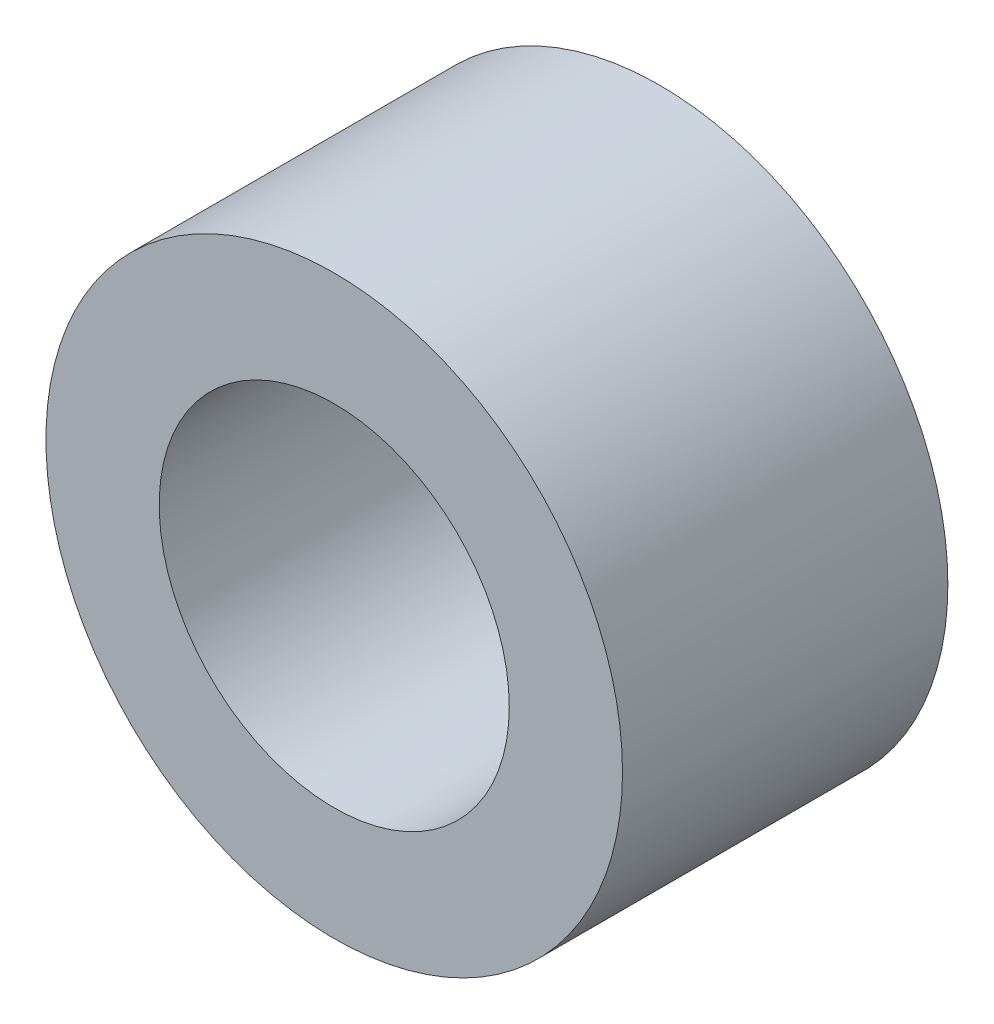
SolidWorks part; units mm, degrees
ref_plane "Front Plane" through (0, 0, 0) normal (0, 0, 1) x (1, 0, 0)
ref_plane "Top Plane" through (0, 0, 0) normal (0, 1, 0) x (1, 0, 0)
ref_plane "Right Plane" through (0, 0, 0) normal (1, 0, 0) x (0, 0, -1)
sketch "Sketch2" plane through (0, 0, 0) normal (0, 0, 1) x (1, 0, 0)
  circle A0 centre (0, 0) radius 4.25
  circle A1 centre (0, 0) radius 7
  dimension "D1" = 8.5
  dimension "D2" = 14
extrude "Boss-Extrude1" add sketch "Sketch2" along normal blind 7.9
